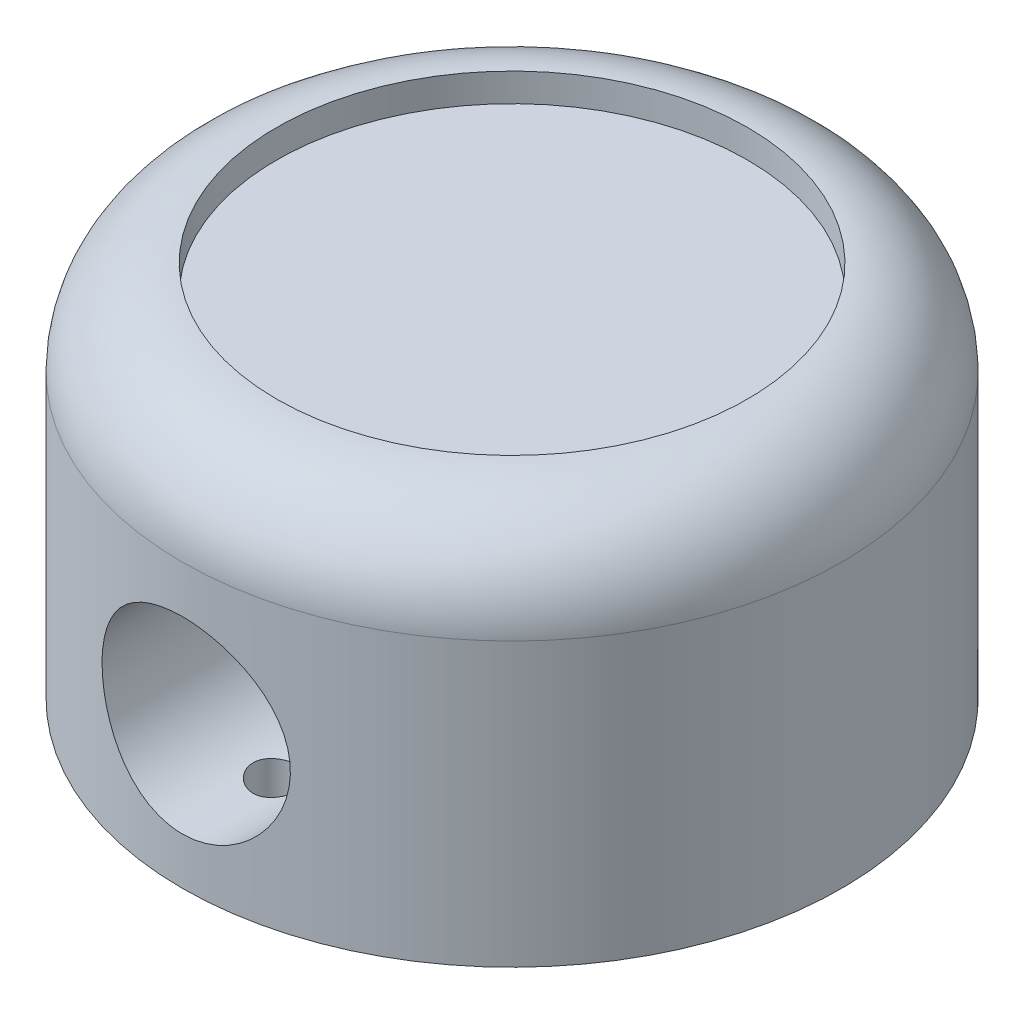
SolidWorks part; units mm, degrees
ref_plane "Plan de face" through (0, 0, 0) normal (0, 0, 1) x (1, 0, 0)
ref_plane "Plan de dessus" through (0, 0, 0) normal (0, 1, 0) x (1, 0, 0)
ref_plane "Plan de droite" through (0, 0, 0) normal (1, 0, 0) x (0, 0, -1)
sketch "Esquisse2" plane through (0, 0, 0) normal (0, 1, 0) x (1, 0, 0)
  circle A0 centre (0, 0) radius 35
extrude "Boss.-Extru.1" add sketch "Esquisse2" along normal blind 40 contours A0
fillet "Congé1" radius 10 1 edges at (0, 40, 35)
sketch "Esquisse3" plane through (0, 0, 0) normal (0, -1, 0) x (1, 0, 0)
  circle A0 centre (0, 0) radius 20
extrude "Enlèv. mat.-Extru.1" cut sketch "Esquisse3" against normal blind 30
sketch "Esquisse4" plane through (0, 0, 0) normal (0, -1, 0) x (1, 0, 0)
  line L0 (0, 0) -> (0, 25) construction
  circle A0 centre (0, 25) radius 2.5
sketch "Esquisse7" plane through (0, 40, 0) normal (0, 1, 0) x (1, 0, 0)
  circle A0 centre (0, 0) radius 25
extrude "Enlèv. mat.-Extru.3" cut sketch "Esquisse7" against normal blind 3
sketch "Esquisse8" plane through (0, 0, 0) normal (0, 0, 1) x (1, 0, 0)
  line L1 (0, 30) -> (0, 0) construction
  line L2 (-35, 30) -> (35, 30) construction
  circle A0 centre (0, 15) radius 10
extrude "Enlèv. mat.-Extru.4" cut sketch "Esquisse8" along normal blind 45
extrude "Enlèv. mat.-Extru.5" cut sketch "Esquisse4" against normal blind 30 contours A0
sketch "Esquisse9" plane through (0, 0, 0) normal (0, -1, 0) x (1, 0, 0)
  line L0 (20, 0) -> (35, 0) construction
  line L2 (-20, 0) -> (-35, 0) construction
  line L3 (-20, 0) -> (-35, 0) construction
  circle A0 centre (0, 0) radius 35 construction
  circle A1 centre (0, 0) radius 20 construction
  circle A2 centre (-27.5, 0) radius 1.5
  circle A3 centre (0, 0) radius 20 construction
  circle A4 centre (27.5, 0) radius 1.5
extrude "Enlèv. mat.-Extru.6" cut sketch "Esquisse9" against normal blind 16
